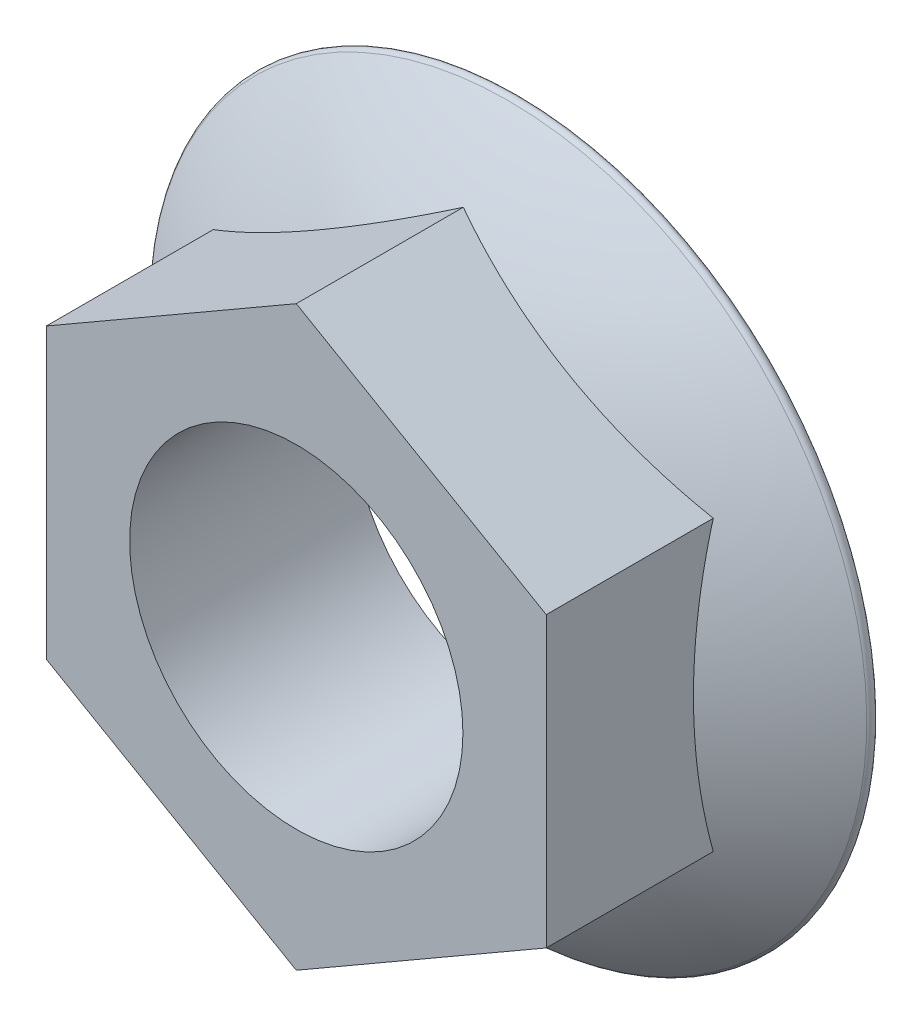
SolidWorks part; units mm, degrees
ref_plane "Front Plane" through (0, 0, 0) normal (0, 0, 1) x (1, 0, 0)
ref_plane "Top Plane" through (0, 0, 0) normal (0, 1, 0) x (1, 0, 0)
ref_plane "Right Plane" through (0, 0, 0) normal (1, 0, 0) x (0, 0, -1)
sketch "Sketch1" plane through (0, 0, 0) normal (0, 0, 1) x (1, 0, 0)
  line L1 (22.5, 12.9904) -> (0, 25.9808)
  line L2 (0, 25.9808) -> (-22.5, 12.9904)
  line L3 (-22.5, 12.9904) -> (-22.5, -12.9904)
  line L4 (-22.5, -12.9904) -> (0, -25.9808)
  line L5 (0, -25.9808) -> (22.5, -12.9904)
  line L6 (22.5, -12.9904) -> (22.5, 12.9904)
  circle A0 centre (0, 0) radius 22.5 construction
  dimension "D1" = 45
extrude "Boss-Extrude2" add sketch "Sketch1" along normal blind 20
sketch "Sketch2" plane through (0, 0, 0) normal (1, 0, 0) x (0, 0, -1)
  line L0 (0, 0) -> (-12, 0)
  line L1 (0, 0) -> (0, -31.95)
  arc A0 (-0.9002, -32.2497) -> (-12, 0) centre (43.6762, 1.1277) cw
  arc A1 (0, -31.95) -> (-0.9002, -32.2497) centre (-0.5, -31.95) cw
  dimension "D2" = 0.5
  dimension "D1" = 12
  dimension "D3" = 31.95
revolve "Revolve1" add sketch "Sketch2" angle 360 about L0
sketch "Sketch3" plane through (0, 0, 20) normal (0, 0, 1) x (1, 0, 0)
  circle A0 centre (0, 0) radius 15
extrude "Cut-Extrude1" cut sketch "Sketch3" against normal through all
cosmetic thread "Cosmetic Thread1" parameters "D2"=31.75
